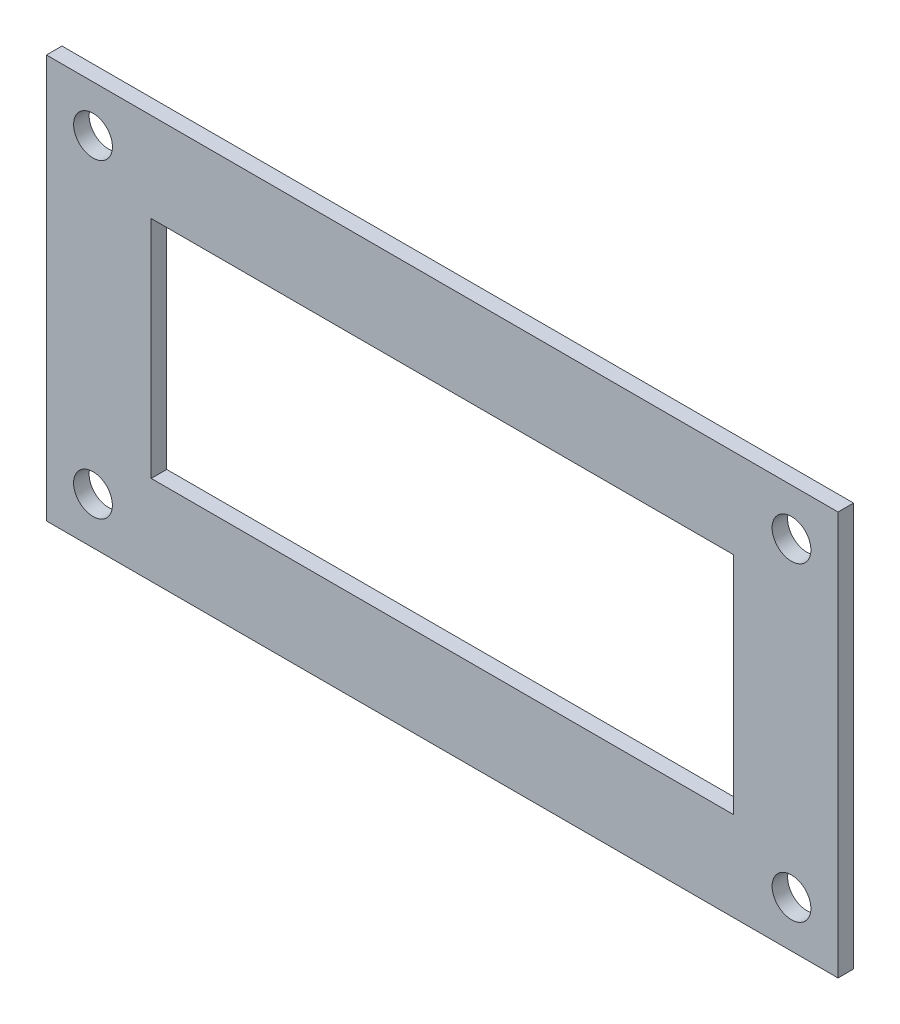
SolidWorks part; units mm, degrees
ref_plane "Front Plane" through (0, 0, 0) normal (0, 0, 1) x (1, 0, 0)
ref_plane "Top Plane" through (0, 0, 0) normal (0, 1, 0) x (1, 0, 0)
ref_plane "Right Plane" through (0, 0, 0) normal (1, 0, 0) x (0, 0, -1)
sketch "Sketch1" plane through (0, 0, 0) normal (0, 0, 1) x (1, 0, 0)
  line L0 (0, 0) -> (0, 21.4084) construction
  line L1 (-37.5, -14.5) -> (37.5, -14.5)
  line L2 (-37.5, -14.5) -> (-37.5, 14.5)
  line L3 (-37.5, 14.5) -> (37.5, 14.5)
  line L4 (37.5, -14.5) -> (37.5, 14.5)
  line L5 (-37.5, -14.5) -> (37.5, 14.5) construction
  line L6 (-37.5, 14.5) -> (37.5, -14.5) construction
  line L7 (-51, -26) -> (51, -26)
  line L8 (-51, -26) -> (-51, 26)
  line L9 (-51, 26) -> (51, 26)
  line L10 (51, -26) -> (51, 26)
  line L11 (-51, -26) -> (51, 26) construction
  line L12 (-51, 26) -> (51, -26) construction
  line L13 (-20.0501, 0) -> (26.9162, 0) construction
  circle A0 centre (-45, 20) radius 2.5
  circle A1 centre (45, 20) radius 2.5
  circle A2 centre (45, -20) radius 2.5
  circle A3 centre (-45, -20) radius 2.5
  point P0 (0, 0)
  point P6 (0, 0)
  dimension "D5" = 5
  dimension "D1" = 75
  dimension "D2" = 29
  dimension "D3" = 102
  dimension "D4" = 52
  dimension "D6" = 6
  dimension "D7" = 6
extrude "Boss-Extrude2" add sketch "Sketch1" along normal blind 2
